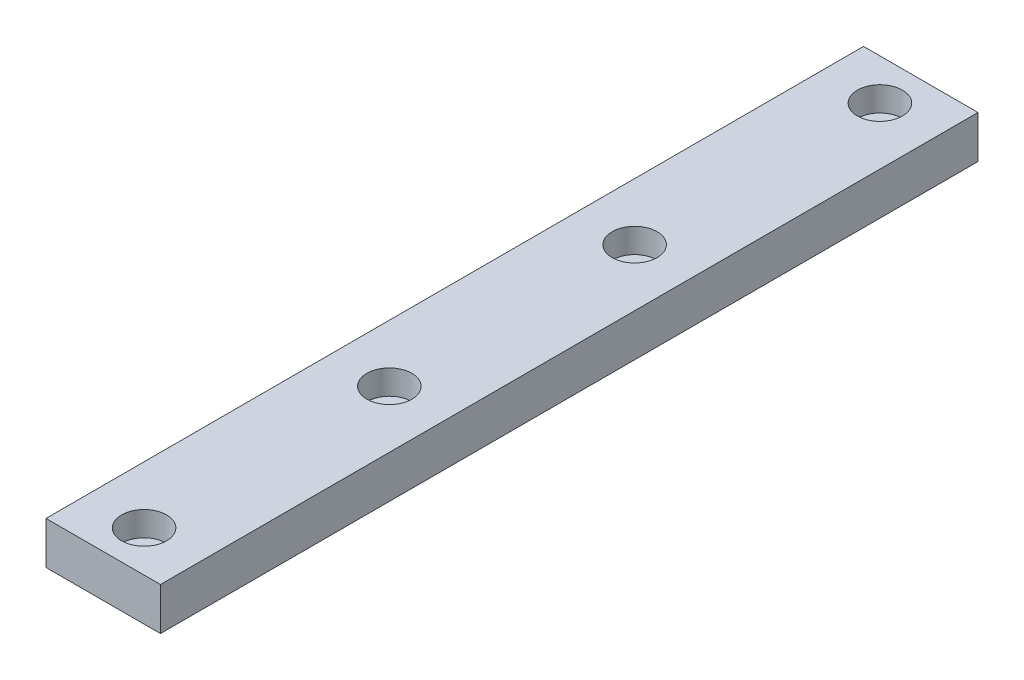
SolidWorks part; units mm, degrees
ref_plane "前视基准面" through (0, 0, 0) normal (0, 0, 1) x (1, 0, 0)
ref_plane "上视基准面" through (0, 0, 0) normal (0, 1, 0) x (1, 0, 0)
ref_plane "右视基准面" through (0, 0, 0) normal (1, 0, 0) x (0, 0, -1)
sketch "草图1" plane through (0, 0, 0) normal (0, 0, 1) x (1, 0, 0)
  line L1 (-7, -2.6) -> (7, -2.6)
  line L2 (-7, -2.6) -> (-7, 2.6)
  line L3 (-7, 2.6) -> (7, 2.6)
  line L4 (7, -2.6) -> (7, 2.6)
  line L5 (-7, -2.6) -> (7, 2.6) construction
  line L6 (-7, 2.6) -> (7, -2.6) construction
  point P0 (0, 0)
  dimension "D1" = 14
  dimension "D2" = 5.2
extrude "凸台-拉伸1" add sketch "草图1" along normal mid plane 100
sketch "草图2" plane through (0, 0, 0) normal (0, 1, 0) x (1, 0, 0)
  line L0 (0, -55.1755) -> (0, 53.5014) construction
sketch "草图3" plane through (0, 2.6, 0) normal (0, 1, 0) x (1, 0, 0)
  line L0 (0, -55.1755) -> (0, 53.5014) construction
  circle A0 centre (0, -45) radius 2.75
  circle A1 centre (0, -15) radius 2.75
  circle A2 centre (0, 15) radius 2.75
  circle A3 centre (0, 45) radius 2.75
  dimension "D2" = 5.5
  dimension "D1" = 45
  dimension "D3" = 4
extrude "切除-拉伸1" cut sketch "草图3" against normal blind 3
sketch "草图4" plane through (0, 2.6, 0) normal (0, 1, 0) x (1, 0, 0)
  circle A0 centre (0, -45) radius 1.5
  circle A1 centre (0, -15) radius 1.5
  circle A2 centre (0, 15) radius 1.5
  circle A3 centre (0, 45) radius 1.5
  dimension "D1" = 3
  dimension "D3" = 45
  dimension "D4" = 30
  dimension "D2" = 4
extrude "切除-拉伸2" cut sketch "草图4" against normal through all both and the other way through all
